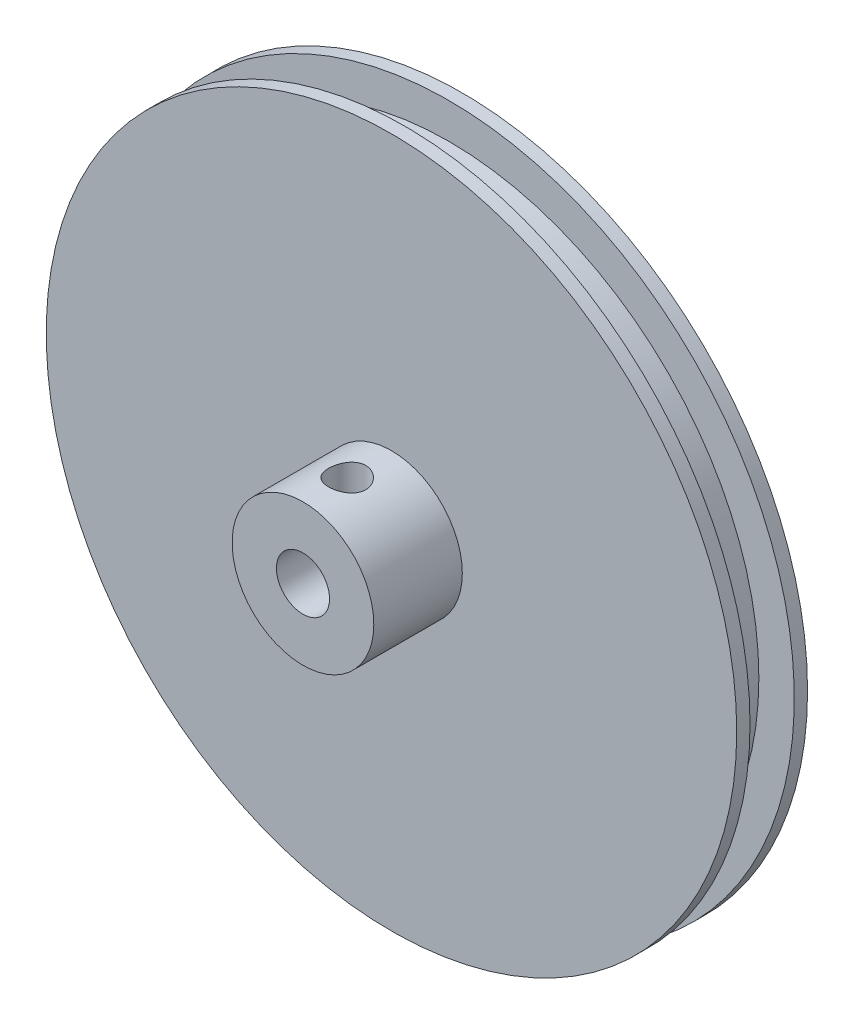
SolidWorks part; units mm, degrees
ref_plane "Front Plane" through (0, 0, 0) normal (0, 0, 1) x (1, 0, 0)
ref_plane "Top Plane" through (0, 0, 0) normal (0, 1, 0) x (1, 0, 0)
ref_plane "Right Plane" through (0, 0, 0) normal (1, 0, 0) x (0, 0, -1)
sketch "Sketch1" plane through (0, 0, 0) normal (0, 0, 1) x (1, 0, 0)
  circle A0 centre (0, 0) radius 39
  dimension "D1" = 78
extrude "Boss-Extrude1" add sketch "Sketch1" along normal blind 8
sketch "Sketch2" plane through (0, 0, 8) normal (0, 0, 1) x (1, 0, 0)
  circle A0 centre (0, 0) radius 8
  dimension "D1" = 16
extrude "Boss-Extrude2" add sketch "Sketch2" along normal blind 10
sketch "Sketch3" plane through (0, 0, 18) normal (0, 0, 1) x (1, 0, 0)
  circle A0 centre (0, 0) radius 3
  dimension "D1" = 6
extrude "Cut-Extrude1" cut sketch "Sketch3" against normal through all
hole_wizard "M5 Tapped Hole1" positions "3DSketch1" profile "Sketch4" tap size "M5" standard "ISO"
sketch3d "3DSketch1"
  line L0 (0, 0, 0) -> (0, 0, 4.8159) construction
  line L2 (2.786, -7.4992, 18) -> (6.0413, -7.4992, 18) construction
  point P0 (-0.0063, 8, 13)
  dimension "D1" = 5
sketch "Sketch4" plane through (-0.0063, 8, 13) normal (0, 0, 1) x (-1, -0.0008, 0)
  line L0 (0, 0) -> (0, 5)
  line L1 (0, 5) -> (2.1, 5)
  line L2 (2.1, 5) -> (2.1, 0)
  line L5 (2.1, 0) -> (0, 0)
  line L11 (0, -6.35) -> (0, 107.95) construction
  dimension "Thru Tap Drill Dia." = 4.2
  dimension "Thru Tap Drill Depth" = 5
cosmetic thread "Hole Thread1" parameters "D2"=5
sketch "Sketch5" plane through (0, 0, 0) normal (0, 1, 0) x (1, 0, 0)
  line L0 (-39, -4) -> (-36.5201, -4) construction
  line L2 (-39, 0) -> (-39, -8) construction
  line L3 (-43, -1.5) -> (-35, -1.5)
  line L4 (-43, -1.5) -> (-43, -6.5)
  line L5 (-43, -6.5) -> (-35, -6.5)
  line L6 (-35, -1.5) -> (-35, -6.5)
  line L7 (-43, -1.5) -> (-35, -6.5) construction
  line L8 (-43, -6.5) -> (-35, -1.5) construction
  line L9 (0, 0) -> (0, -7.4459) construction
  point P1 (-39, -4)
  dimension "D1" = 4
  dimension "D2" = 5
revolve "Cut-Revolve1" cut sketch "Sketch5" angle 360 about L9
